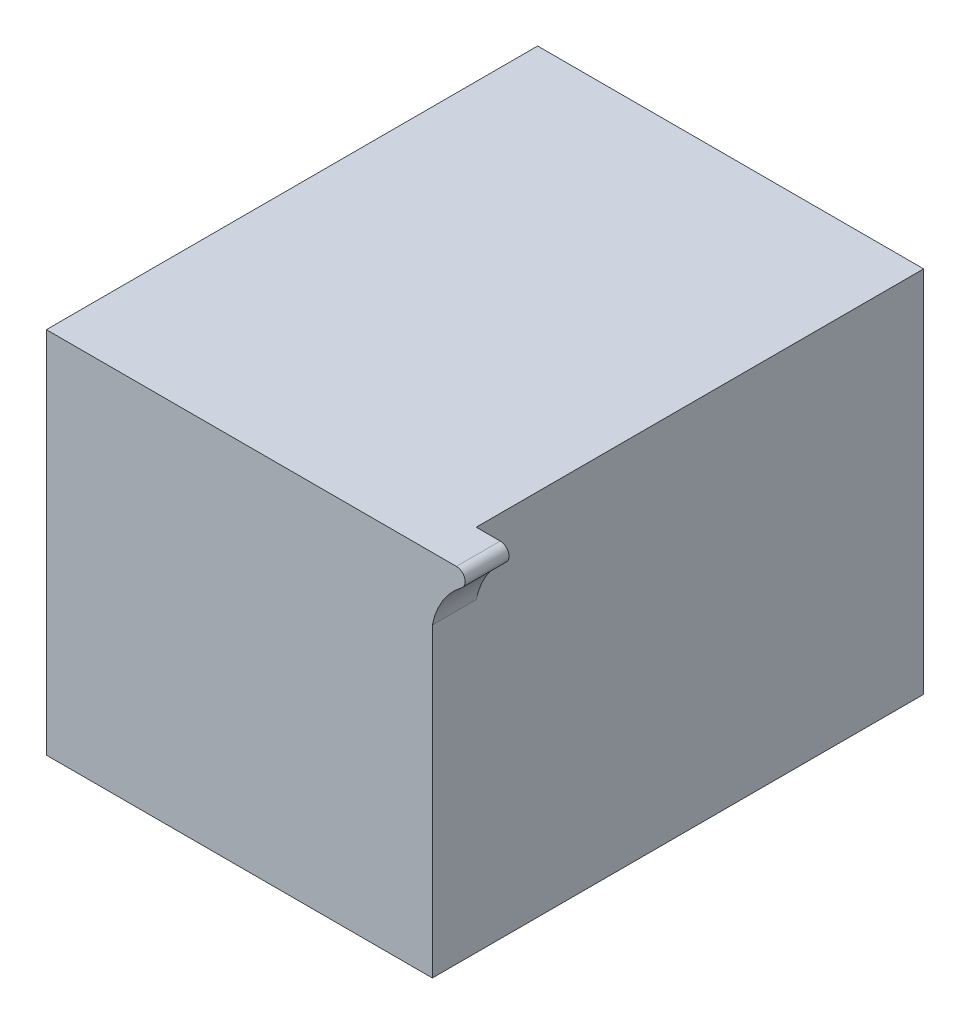
SolidWorks part; units mm, degrees
ref_plane "Front Plane" through (0, 0, 0) normal (0, 0, 1) x (1, 0, 0)
ref_plane "Top Plane" through (0, 0, 0) normal (0, 1, 0) x (1, 0, 0)
ref_plane "Right Plane" through (0, 0, 0) normal (1, 0, 0) x (0, 0, -1)
sketch "Sketch1" plane through (0, 0, 0) normal (0, 0, 1) x (1, 0, 0)
  line L1 (0, 0) -> (44, 0)
  line L2 (0, 0) -> (0, 42)
  line L3 (0, 42) -> (44, 42)
  line L4 (44, 0) -> (44, 42)
  line L5 (0, 0) -> (44, 42) construction
  line L6 (0, 42) -> (44, 0) construction
  point P4 (22, 21)
  dimension "D1" = 42
  dimension "D2" = 44
extrude "Boss-Extrude1" add sketch "Sketch1" against normal blind 56
sketch "Sketch2" plane through (0, 0, 0) normal (0, 0, 1) x (1, 0, 0)
  line L0 (44, 42) -> (52.6917, 42)
  line L2 (44, 0) -> (44, 42) construction
  line L3 (44, 34.8522) -> (44, 42)
  arc A0 (52.6917, 42) -> (44, 34.8522) centre (52.6917, 33.1416) ccw
extrude "Boss-Extrude2" add sketch "Sketch2" against normal blind 5
fillet "Fillet1" radius 1 1 edges at (52.6917, 42, -2.5)
